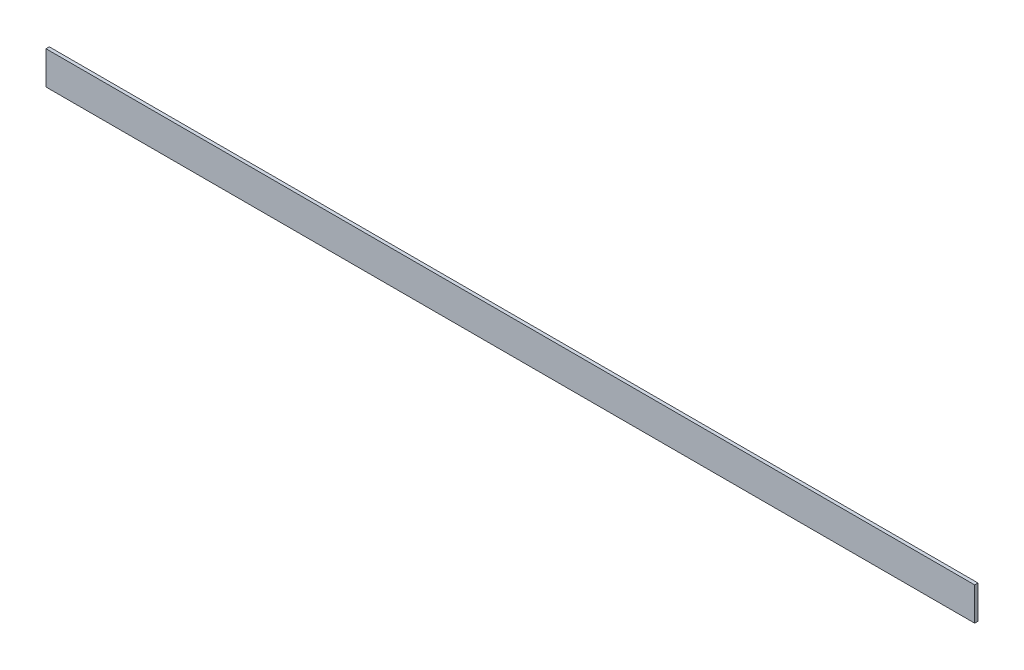
SolidWorks part; units mm, degrees
ref_plane "Front Plane" through (0, 0, 0) normal (0, 0, 1) x (1, 0, 0)
ref_plane "Top Plane" through (0, 0, 0) normal (0, 1, 0) x (1, 0, 0)
ref_plane "Right Plane" through (0, 0, 0) normal (1, 0, 0) x (0, 0, -1)
sketch "Sketch2" plane through (0, 0, 0) normal (0, 0, 1) x (1, 0, 0)
  line L1 (280, -10) -> (-280, -10)
  line L2 (280, -10) -> (280, 10)
  line L3 (280, 10) -> (-280, 10)
  line L4 (-280, -10) -> (-280, 10)
  line L5 (280, -10) -> (-280, 10) construction
  line L6 (280, 10) -> (-280, -10) construction
  point P0 (0, 0)
  dimension "D1" = 20
  dimension "D2" = 560
extrude "Boss-Extrude1" add sketch "Sketch2" along normal blind 2
